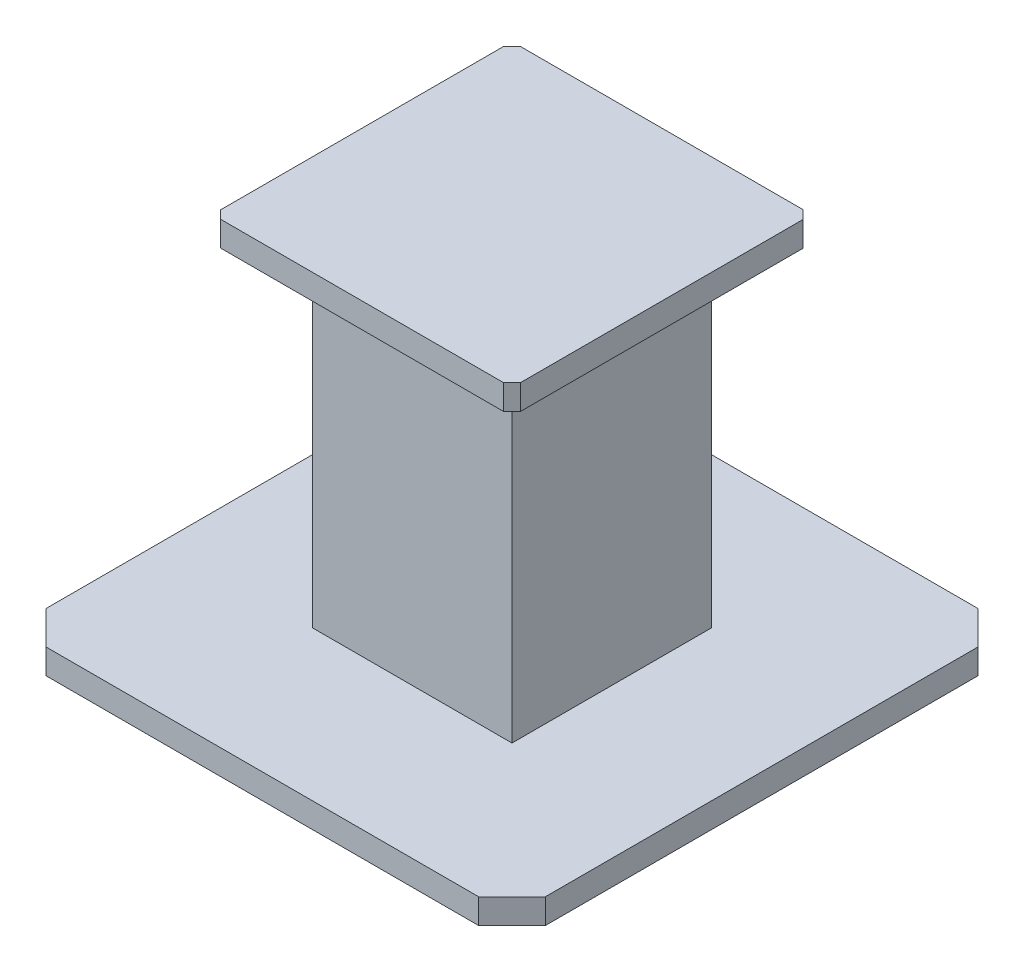
SolidWorks part; units mm, degrees
material "普通碳钢"
ref_plane "前视基准面" through (0, 0, 0) normal (0, 0, 1) x (1, 0, 0)
ref_plane "上视基准面" through (0, 0, 0) normal (0, 1, 0) x (1, 0, 0)
ref_plane "右视基准面" through (0, 0, 0) normal (1, 0, 0) x (0, 0, -1)
sketch "草图1" plane through (0, 0, 0) normal (0, 1, 0) x (1, 0, 0)
  line L1 (90, -90) -> (-90, -90)
  line L2 (90, -90) -> (90, 90)
  line L3 (90, 90) -> (-90, 90)
  line L4 (-90, -90) -> (-90, 90)
  line L5 (90, -90) -> (-90, 90) construction
  line L6 (90, 90) -> (-90, -90) construction
  point P0 (0, 0)
  dimension "D1" = 180
  dimension "D2" = 180
extrude "凸台-拉伸1" add sketch "草图1" along normal blind 15
sketch "草图2" plane through (0, 0, 0) normal (0, -1, 0) x (1, 0, 0)
  line L1 (60, -60) -> (-60, -60)
  line L2 (60, -60) -> (60, 60)
  line L3 (60, 60) -> (-60, 60)
  line L4 (-60, -60) -> (-60, 60)
  line L5 (60, -60) -> (-60, 60) construction
  line L6 (60, 60) -> (-60, -60) construction
  point P0 (0, 0)
  dimension "D1" = 120
  dimension "D2" = 120
extrude "凸台-拉伸2" add sketch "草图2" along normal blind 200
sketch "草图3" plane through (0, -200, 0) normal (0, -1, 0) x (1, 0, 0)
  line L1 (150, -150) -> (-150, -150)
  line L2 (150, -150) -> (150, 150)
  line L3 (150, 150) -> (-150, 150)
  line L4 (-150, -150) -> (-150, 150)
  line L5 (150, -150) -> (-150, 150) construction
  line L6 (150, 150) -> (-150, -150) construction
  point P0 (0, 0)
  dimension "D1" = 300
  dimension "D2" = 300
extrude "凸台-拉伸3" add sketch "草图3" along normal blind 15
chamfer "倒角1" distance 20 angle 45 4 edges at (150, -207.5, -150) (150, -207.5, 150) (-150, -207.5, 150) (-150, -207.5, -150)
chamfer "倒角2" distance 5 angle 45 4 edges at (-90, 7.5, -90) (90, 7.5, -90) (90, 7.5, 90) (-90, 7.5, 90)
